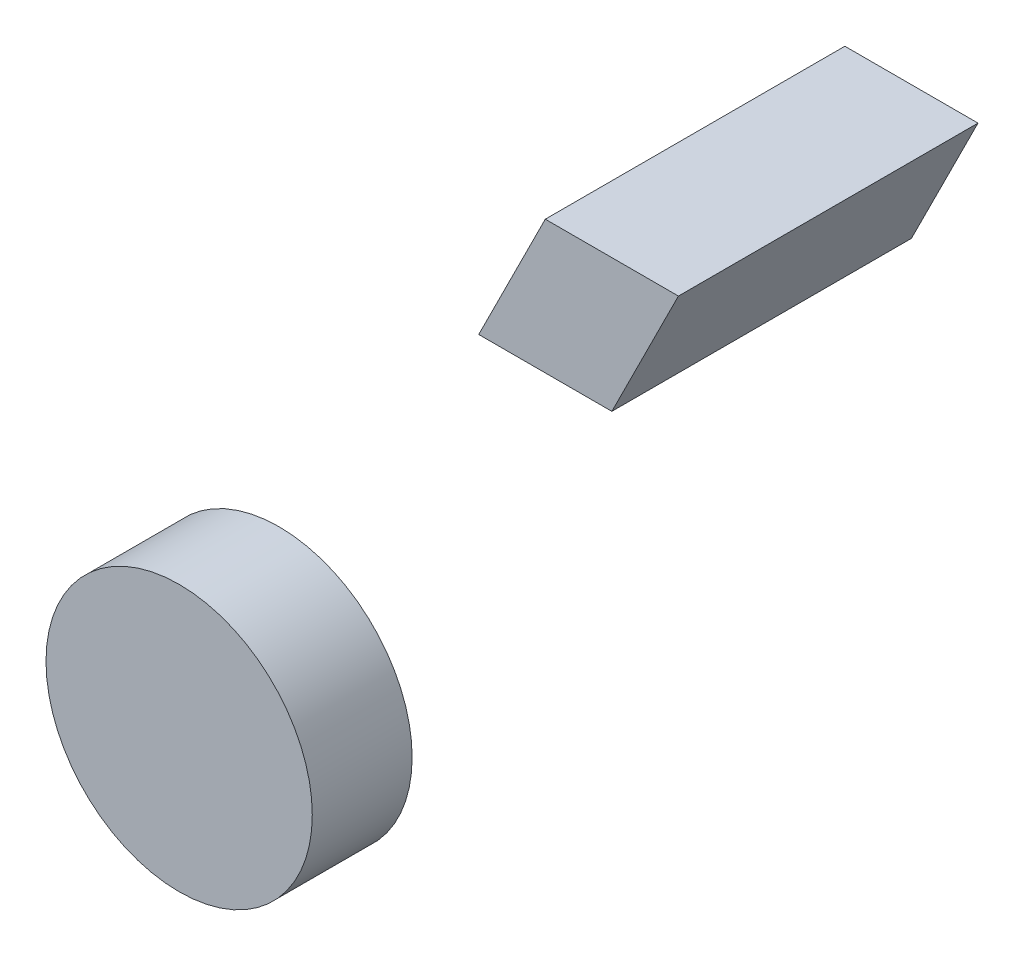
SolidWorks part; units mm, degrees
ref_plane "前视基准面" through (0, 0, 0) normal (0, 0, 1) x (1, 0, 0)
ref_plane "上视基准面" through (0, 0, 0) normal (0, 1, 0) x (1, 0, 0)
ref_plane "右视基准面" through (0, 0, 0) normal (1, 0, 0) x (0, 0, -1)
other "Configuration Table"
sketch "草图1" plane through (0, 0, 0) normal (0, 0, 1) x (1, 0, 0)
  circle A0 centre (0, 0) radius 8
extrude "凸台-拉伸1" add sketch "草图1" along normal blind 24
sketch "草图2" plane through (0, 0, 0) normal (0, 0, 1) x (1, 0, 0)
  circle A0 centre (0, 0) radius 42
extrude "凸台-拉伸2" add sketch "草图2" along normal blind 18
sketch "草图3" plane through (0, 0, 18) normal (0, 0, 1) x (1, 0, 0)
  line L0 (16, 32) -> (24, 32)
  line L1 (24, 32) -> (20, 24)
  line L2 (20, 24) -> (12, 24)
  line L3 (12, 24) -> (16, 32)
extrude "切除-拉伸1" cut sketch "草图3" against normal through all flip side to cut
